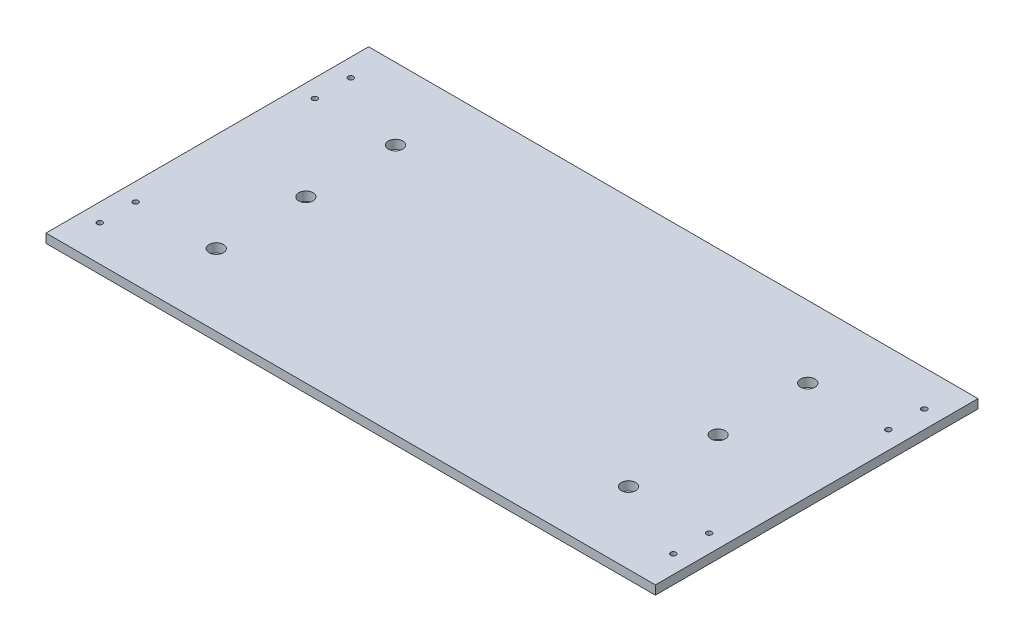
SolidWorks part; units mm, degrees
ref_plane "前视基准面" through (0, 0, 0) normal (0, 0, 1) x (1, 0, 0)
ref_plane "上视基准面" through (0, 0, 0) normal (0, 1, 0) x (1, 0, 0)
ref_plane "右视基准面" through (0, 0, 0) normal (1, 0, 0) x (0, 0, -1)
other "Configuration Table"
sketch "草图1" plane through (0, 0, 0) normal (0, 1, 0) x (1, 0, 0)
  line L1 (0, 0) -> (-340, 0)
  line L2 (0, 0) -> (0, 180)
  line L3 (0, 180) -> (-340, 180)
  line L4 (-340, 0) -> (-340, 180)
  dimension "D1" = 180
  dimension "D2" = 340
extrude "凸台-拉伸1" add sketch "草图1" along normal blind 5
sketch "草图2" plane through (0, 5, 0) normal (0, 1, 0) x (1, 0, 0)
  line L0 (-340, 0) -> (-330, 0) construction
  line L1 (-340, 180) -> (-340, 0) construction
  line L2 (-330, 0) -> (-330, 20) construction
  line L3 (-330, 20) -> (-330, 40) construction
  line L4 (-170, 0) -> (-170, 405.4816) construction
  line L5 (-340, 0) -> (0, 0) construction
  line L6 (-340, 90) -> (129.0484, 90) construction
  line L7 (-330, 160) -> (-330, 140) construction
  line L8 (-330, 180) -> (-330, 160) construction
  line L9 (-340, 180) -> (-330, 180) construction
  line L10 (0, 180) -> (-10, 180) construction
  line L11 (-10, 180) -> (-10, 160) construction
  line L12 (-10, 160) -> (-10, 140) construction
  line L13 (-10, 20) -> (-10, 40) construction
  line L14 (-10, 0) -> (-10, 20) construction
  line L15 (0, 0) -> (-10, 0) construction
  circle A8 centre (-330, 20) radius 1.5
  circle A9 centre (-330, 40) radius 1.5
  circle A10 centre (-330, 140) radius 1.5
  circle A11 centre (-330, 160) radius 1.5
  circle A12 centre (-10, 160) radius 1.5
  circle A13 centre (-10, 140) radius 1.5
  circle A14 centre (-10, 40) radius 1.5
  circle A15 centre (-10, 20) radius 1.5
  dimension "D4" = 3
  dimension "D5" = 3
  dimension "D1" = 10
  dimension "D2" = 20
  dimension "D3" = 20
  dimension "D6" = 10
extrude "切除-拉伸1" cut sketch "草图2" against normal blind 5
sketch "草图4" plane through (0, 5, 0) normal (0, 1, 0) x (1, 0, 0)
  line L0 (-340, 90) -> (-285, 90) construction
  line L1 (-340, 180) -> (-340, 0) construction
  line L2 (-285, 90) -> (-285, 140) construction
  line L3 (-285, 90) -> (-285, 40) construction
  line L4 (-170, 180) -> (-170, -13.5503) construction
  line L5 (0, 180) -> (-340, 180) construction
  line L6 (-55, 90) -> (-55, 40) construction
  line L7 (-55, 90) -> (-55, 140) construction
  line L8 (0, 90) -> (-55, 90) construction
  circle A0 centre (-285, 140) radius 4
  circle A1 centre (-285, 90) radius 4
  circle A2 centre (-285, 40) radius 4
  circle A3 centre (-55, 40) radius 4
  circle A4 centre (-55, 90) radius 4
  circle A5 centre (-55, 140) radius 4
  dimension "D4" = 8
  dimension "D5" = 8
  dimension "D6" = 8
  dimension "D1" = 55
  dimension "D2" = 50
  dimension "D3" = 50
extrude "切除-拉伸2" cut sketch "草图4" against normal blind 5
